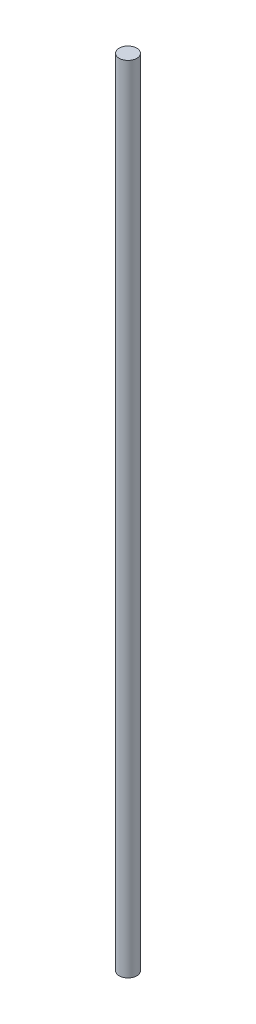
SolidWorks part; units mm, degrees
ref_plane "Front Plane" through (0, 0, 0) normal (0, 0, 1) x (1, 0, 0)
ref_plane "Top Plane" through (0, 0, 0) normal (0, 1, 0) x (1, 0, 0)
ref_plane "Right Plane" through (0, 0, 0) normal (1, 0, 0) x (0, 0, -1)
sketch "Sketch1" plane through (0, 0, 0) normal (0, 1, 0) x (1, 0, 0)
  circle A0 centre (0, 0) radius 5
  dimension "D1" = 10
extrude "Boss-Extrude2" add sketch "Sketch1" along normal blind 450
